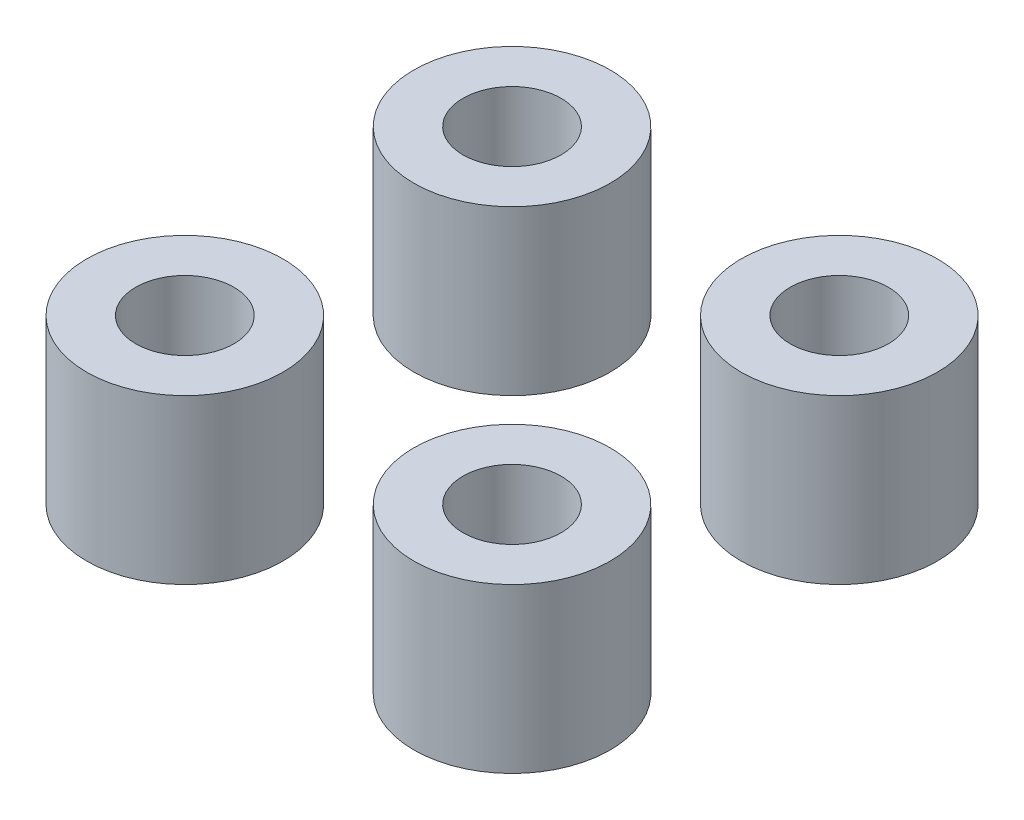
SolidWorks part; units mm, degrees
ref_plane "Спереди" through (0, 0, 0) normal (0, 0, 1) x (1, 0, 0)
ref_plane "Сверху" through (0, 0, 0) normal (0, 1, 0) x (1, 0, 0)
ref_plane "Справа" through (0, 0, 0) normal (1, 0, 0) x (0, 0, -1)
sketch "Эскиз1" plane through (0, 0, 0) normal (0, 1, 0) x (1, 0, 0)
  circle A0 centre (0, 0) radius 3
  circle A1 centre (0, 0) radius 6
  circle A2 centre (0, 20) radius 3
  circle A3 centre (0, 20) radius 6
  circle A4 centre (20, 20) radius 3
  circle A5 centre (20, 20) radius 6
  circle A6 centre (20, 0) radius 3
  circle A7 centre (20, 0) radius 6
extrude "Бобышка-Вытянуть1" add sketch "Эскиз1" along normal blind 10
